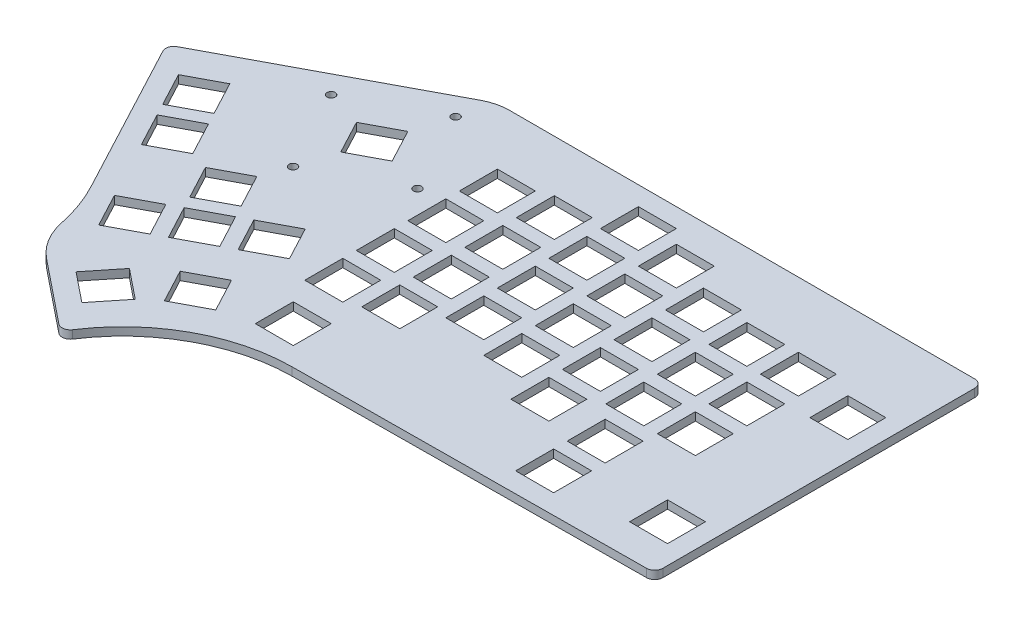
SolidWorks part; units mm, degrees
ref_plane "Front Plane" through (0, 0, 0) normal (0, 0, 1) x (1, 0, 0)
ref_plane "Top Plane" through (0, 0, 0) normal (0, 1, 0) x (1, 0, 0)
ref_plane "Right Plane" through (0, 0, 0) normal (1, 0, 0) x (0, 0, -1)
sketch "Main" plane through (0, 0, 0) normal (0, 1, 0) x (1, 0, 0)
  line L0 (6.4754, 3.5) -> (12.8, 6.5) construction
  line L1 (0, 0) -> (18, 0) construction
  line L2 (0, 0) -> (0, 18) construction
  line L3 (0, 18) -> (18, 18) construction
  line L4 (18, 0) -> (18, 18) construction
  line L5 (2, 16) -> (16, 16)
  line L6 (2, 16) -> (2, 2)
  line L7 (2, 2) -> (16, 2)
  line L8 (16, 16) -> (16, 2)
  line L18 (9, 9) -> (6.4754, 3.5) construction
  line L20 (9, 9) -> (12.8, 6.5) construction
  line L22 (25.4754, 5.5) -> (31.8, 8.5) construction
  line L23 (19, 2) -> (37, 2) construction
  line L24 (19, 2) -> (19, 20) construction
  line L25 (19, 20) -> (37, 20) construction
  line L26 (37, 2) -> (37, 20) construction
  line L27 (21, 18) -> (35, 18)
  line L28 (21, 18) -> (21, 4)
  line L29 (21, 4) -> (35, 4)
  line L30 (35, 18) -> (35, 4)
  line L31 (28, 11) -> (25.4754, 5.5) construction
  line L32 (28, 11) -> (31.8, 8.5) construction
  line L33 (44.4754, 17.5) -> (50.8, 20.5) construction
  line L34 (38, 14) -> (56, 14) construction
  line L35 (38, 14) -> (38, 32) construction
  line L36 (38, 32) -> (56, 32) construction
  line L37 (56, 14) -> (56, 32) construction
  line L38 (40, 30) -> (54, 30)
  line L39 (40, 30) -> (40, 16)
  line L40 (40, 16) -> (54, 16)
  line L41 (54, 30) -> (54, 16)
  line L42 (47, 23) -> (44.4754, 17.5) construction
  line L43 (47, 23) -> (50.8, 20.5) construction
  line L44 (63.4754, 12.5) -> (69.8, 15.5) construction
  line L45 (57, 9) -> (75, 9) construction
  line L46 (57, 9) -> (57, 27) construction
  line L47 (57, 27) -> (75, 27) construction
  line L48 (75, 9) -> (75, 27) construction
  line L49 (59, 25) -> (73, 25)
  line L50 (59, 25) -> (59, 11)
  line L51 (59, 11) -> (73, 11)
  line L52 (73, 25) -> (73, 11)
  line L53 (66, 18) -> (63.4754, 12.5) construction
  line L54 (66, 18) -> (69.8, 15.5) construction
  line L55 (82.4754, 3.5) -> (88.8, 6.5) construction
  line L56 (76, 0) -> (94, 0) construction
  line L57 (76, 0) -> (76, 18) construction
  line L58 (76, 18) -> (94, 18) construction
  line L59 (94, 0) -> (94, 18) construction
  line L60 (78, 16) -> (92, 16)
  line L61 (78, 16) -> (78, 2)
  line L62 (78, 2) -> (92, 2)
  line L63 (92, 16) -> (92, 2)
  line L64 (85, 9) -> (82.4754, 3.5) construction
  line L65 (85, 9) -> (88.8, 6.5) construction
  line L66 (101.4754, 0.5) -> (107.8, 3.5) construction
  line L67 (95, -3) -> (113, -3) construction
  line L68 (95, -3) -> (95, 15) construction
  line L69 (95, 15) -> (113, 15) construction
  line L70 (113, -3) -> (113, 15) construction
  line L71 (97, 13) -> (111, 13)
  line L72 (97, 13) -> (97, -1)
  line L73 (97, -1) -> (111, -1)
  line L74 (111, 13) -> (111, -1)
  line L75 (104, 6) -> (101.4754, 0.5) construction
  line L76 (104, 6) -> (107.8, 3.5) construction
  line L77 (120.4754, 0.5) -> (126.8, 3.5) construction
  line L78 (114, -3) -> (132, -3) construction
  line L79 (114, -3) -> (114, 15) construction
  line L80 (114, 15) -> (132, 15) construction
  line L81 (132, -3) -> (132, 15) construction
  line L82 (116, 13) -> (130, 13)
  line L83 (116, 13) -> (116, -1)
  line L84 (116, -1) -> (130, -1)
  line L85 (130, 13) -> (130, -1)
  line L86 (123, 6) -> (120.4754, 0.5) construction
  line L87 (123, 6) -> (126.8, 3.5) construction
  line L88 (2, -3) -> (16, -3)
  line L89 (2, -3) -> (2, -17)
  line L90 (2, -17) -> (16, -17)
  line L91 (16, -3) -> (16, -17)
  line L92 (21, -1) -> (35, -1)
  line L93 (21, -1) -> (21, -15)
  line L94 (21, -15) -> (35, -15)
  line L95 (35, -1) -> (35, -15)
  line L96 (40, 11) -> (54, 11)
  line L97 (40, 11) -> (40, -3)
  line L98 (40, -3) -> (54, -3)
  line L99 (54, 11) -> (54, -3)
  line L100 (59, 6) -> (73, 6)
  line L101 (59, 6) -> (59, -8)
  line L102 (59, -8) -> (73, -8)
  line L103 (73, 6) -> (73, -8)
  line L104 (78, -3) -> (92, -3)
  line L105 (78, -3) -> (78, -17)
  line L106 (78, -17) -> (92, -17)
  line L107 (92, -3) -> (92, -17)
  line L108 (97, -6) -> (111, -6)
  line L109 (97, -6) -> (97, -20)
  line L110 (97, -20) -> (111, -20)
  line L111 (111, -6) -> (111, -20)
  line L112 (116, -6) -> (130, -6)
  line L113 (116, -6) -> (116, -20)
  line L114 (116, -20) -> (130, -20)
  line L115 (130, -6) -> (130, -20)
  line L116 (6.4754, -15.5) -> (12.8, -12.5) construction
  line L117 (0, -19) -> (18, -19) construction
  line L118 (0, -19) -> (0, -1) construction
  line L119 (0, -1) -> (18, -1) construction
  line L120 (18, -19) -> (18, -1) construction
  line L121 (9, -10) -> (6.4754, -15.5) construction
  line L122 (9, -10) -> (12.8, -12.5) construction
  line L123 (25.4754, -13.5) -> (31.8, -10.5) construction
  line L124 (19, -17) -> (37, -17) construction
  line L125 (19, -17) -> (19, 1) construction
  line L126 (19, 1) -> (37, 1) construction
  line L127 (37, -17) -> (37, 1) construction
  line L128 (28, -8) -> (25.4754, -13.5) construction
  line L129 (28, -8) -> (31.8, -10.5) construction
  line L130 (44.4754, -1.5) -> (50.8, 1.5) construction
  line L131 (38, -5) -> (56, -5) construction
  line L132 (38, -5) -> (38, 13) construction
  line L133 (38, 13) -> (56, 13) construction
  line L134 (56, -5) -> (56, 13) construction
  line L135 (47, 4) -> (44.4754, -1.5) construction
  line L136 (47, 4) -> (50.8, 1.5) construction
  line L137 (63.4754, -6.5) -> (69.8, -3.5) construction
  line L138 (57, -10) -> (75, -10) construction
  line L139 (57, -10) -> (57, 8) construction
  line L140 (57, 8) -> (75, 8) construction
  line L141 (75, -10) -> (75, 8) construction
  line L142 (66, -1) -> (63.4754, -6.5) construction
  line L143 (66, -1) -> (69.8, -3.5) construction
  line L144 (82.4754, -15.5) -> (88.8, -12.5) construction
  line L145 (76, -19) -> (94, -19) construction
  line L146 (76, -19) -> (76, -1) construction
  line L147 (76, -1) -> (94, -1) construction
  line L148 (94, -19) -> (94, -1) construction
  line L149 (85, -10) -> (82.4754, -15.5) construction
  line L150 (85, -10) -> (88.8, -12.5) construction
  line L151 (101.4754, -18.5) -> (107.8, -15.5) construction
  line L152 (95, -22) -> (113, -22) construction
  line L153 (95, -22) -> (95, -4) construction
  line L154 (95, -4) -> (113, -4) construction
  line L155 (113, -22) -> (113, -4) construction
  line L156 (104, -13) -> (101.4754, -18.5) construction
  line L157 (104, -13) -> (107.8, -15.5) construction
  line L158 (120.4754, -18.5) -> (126.8, -15.5) construction
  line L159 (114, -22) -> (132, -22) construction
  line L160 (114, -22) -> (114, -4) construction
  line L161 (114, -4) -> (132, -4) construction
  line L162 (132, -22) -> (132, -4) construction
  line L163 (123, -13) -> (120.4754, -18.5) construction
  line L164 (123, -13) -> (126.8, -15.5) construction
  line L165 (2, -22) -> (16, -22)
  line L166 (2, -22) -> (2, -36)
  line L167 (2, -36) -> (16, -36)
  line L168 (16, -22) -> (16, -36)
  line L169 (21, -20) -> (35, -20)
  line L170 (21, -20) -> (21, -34)
  line L171 (21, -34) -> (35, -34)
  line L172 (35, -20) -> (35, -34)
  line L173 (40, -8) -> (54, -8)
  line L174 (40, -8) -> (40, -22)
  line L175 (40, -22) -> (54, -22)
  line L176 (54, -8) -> (54, -22)
  line L177 (59, -13) -> (73, -13)
  line L178 (59, -13) -> (59, -27)
  line L179 (59, -27) -> (73, -27)
  line L180 (73, -13) -> (73, -27)
  line L181 (78, -22) -> (92, -22)
  line L182 (78, -22) -> (78, -36)
  line L183 (78, -36) -> (92, -36)
  line L184 (92, -22) -> (92, -36)
  line L185 (97, -25) -> (111, -25)
  line L186 (97, -25) -> (97, -39)
  line L187 (97, -39) -> (111, -39)
  line L188 (111, -25) -> (111, -39)
  line L189 (116, -25) -> (130, -25)
  line L190 (116, -25) -> (116, -39)
  line L191 (116, -39) -> (130, -39)
  line L192 (130, -25) -> (130, -39)
  line L193 (6.4754, -34.5) -> (12.8, -31.5) construction
  line L194 (0, -38) -> (18, -38) construction
  line L195 (0, -38) -> (0, -20) construction
  line L196 (0, -20) -> (18, -20) construction
  line L197 (18, -38) -> (18, -20) construction
  line L198 (9, -29) -> (6.4754, -34.5) construction
  line L199 (9, -29) -> (12.8, -31.5) construction
  line L200 (25.4754, -32.5) -> (31.8, -29.5) construction
  line L201 (19, -36) -> (37, -36) construction
  line L202 (19, -36) -> (19, -18) construction
  line L203 (19, -18) -> (37, -18) construction
  line L204 (37, -36) -> (37, -18) construction
  line L205 (28, -27) -> (25.4754, -32.5) construction
  line L206 (28, -27) -> (31.8, -29.5) construction
  line L207 (44.4754, -20.5) -> (50.8, -17.5) construction
  line L208 (38, -24) -> (56, -24) construction
  line L209 (38, -24) -> (38, -6) construction
  line L210 (38, -6) -> (56, -6) construction
  line L211 (56, -24) -> (56, -6) construction
  line L212 (47, -15) -> (44.4754, -20.5) construction
  line L213 (47, -15) -> (50.8, -17.5) construction
  line L214 (63.4754, -25.5) -> (69.8, -22.5) construction
  line L215 (57, -29) -> (75, -29) construction
  line L216 (57, -29) -> (57, -11) construction
  line L217 (57, -11) -> (75, -11) construction
  line L218 (75, -29) -> (75, -11) construction
  line L219 (66, -20) -> (63.4754, -25.5) construction
  line L220 (66, -20) -> (69.8, -22.5) construction
  line L221 (82.4754, -34.5) -> (88.8, -31.5) construction
  line L222 (76, -38) -> (94, -38) construction
  line L223 (76, -38) -> (76, -20) construction
  line L224 (76, -20) -> (94, -20) construction
  line L225 (94, -38) -> (94, -20) construction
  line L226 (85, -29) -> (82.4754, -34.5) construction
  line L227 (85, -29) -> (88.8, -31.5) construction
  line L228 (101.4754, -37.5) -> (107.8, -34.5) construction
  line L229 (95, -41) -> (113, -41) construction
  line L230 (95, -41) -> (95, -23) construction
  line L231 (95, -23) -> (113, -23) construction
  line L232 (113, -41) -> (113, -23) construction
  line L233 (104, -32) -> (101.4754, -37.5) construction
  line L234 (104, -32) -> (107.8, -34.5) construction
  line L235 (120.4754, -37.5) -> (126.8, -34.5) construction
  line L236 (114, -41) -> (132, -41) construction
  line L237 (114, -41) -> (114, -23) construction
  line L238 (114, -23) -> (132, -23) construction
  line L239 (132, -41) -> (132, -23) construction
  line L240 (123, -32) -> (120.4754, -37.5) construction
  line L241 (123, -32) -> (126.8, -34.5) construction
  line L242 (2, -41) -> (16, -41)
  line L243 (2, -41) -> (2, -55)
  line L244 (2, -55) -> (16, -55)
  line L245 (16, -41) -> (16, -55)
  line L246 (21, -39) -> (35, -39)
  line L247 (21, -39) -> (21, -53)
  line L248 (21, -53) -> (35, -53)
  line L249 (35, -39) -> (35, -53)
  line L250 (40, -27) -> (54, -27)
  line L251 (40, -27) -> (40, -41)
  line L252 (40, -41) -> (54, -41)
  line L253 (54, -27) -> (54, -41)
  line L254 (59, -32) -> (73, -32)
  line L255 (59, -32) -> (59, -46)
  line L256 (59, -46) -> (73, -46)
  line L257 (73, -32) -> (73, -46)
  line L258 (78, -41) -> (92, -41)
  line L259 (78, -41) -> (78, -55)
  line L260 (78, -55) -> (92, -55)
  line L261 (92, -41) -> (92, -55)
  line L270 (6.4754, -53.5) -> (12.8, -50.5) construction
  line L271 (0, -57) -> (18, -57) construction
  line L272 (0, -57) -> (0, -39) construction
  line L273 (0, -39) -> (18, -39) construction
  line L274 (18, -57) -> (18, -39) construction
  line L275 (9, -48) -> (6.4754, -53.5) construction
  line L276 (9, -48) -> (12.8, -50.5) construction
  line L277 (25.4754, -51.5) -> (31.8, -48.5) construction
  line L278 (19, -55) -> (37, -55) construction
  line L279 (19, -55) -> (19, -37) construction
  line L280 (19, -37) -> (37, -37) construction
  line L281 (37, -55) -> (37, -37) construction
  line L282 (28, -46) -> (25.4754, -51.5) construction
  line L283 (28, -46) -> (31.8, -48.5) construction
  line L284 (44.4754, -39.5) -> (50.8, -36.5) construction
  line L285 (38, -43) -> (56, -43) construction
  line L286 (38, -43) -> (38, -25) construction
  line L287 (38, -25) -> (56, -25) construction
  line L288 (56, -43) -> (56, -25) construction
  line L289 (47, -34) -> (44.4754, -39.5) construction
  line L290 (47, -34) -> (50.8, -36.5) construction
  line L291 (63.4754, -44.5) -> (69.8, -41.5) construction
  line L292 (57, -48) -> (75, -48) construction
  line L293 (57, -48) -> (57, -30) construction
  line L294 (57, -30) -> (75, -30) construction
  line L295 (75, -48) -> (75, -30) construction
  line L296 (66, -39) -> (63.4754, -44.5) construction
  line L297 (66, -39) -> (69.8, -41.5) construction
  line L298 (82.4754, -53.5) -> (88.8, -50.5) construction
  line L299 (76, -57) -> (94, -57) construction
  line L300 (76, -57) -> (76, -39) construction
  line L301 (76, -39) -> (94, -39) construction
  line L302 (94, -57) -> (94, -39) construction
  line L303 (85, -48) -> (82.4754, -53.5) construction
  line L304 (85, -48) -> (88.8, -50.5) construction
  line L319 (97, -44) -> (111, -44)
  line L320 (97, -44) -> (97, -58)
  line L321 (97, -58) -> (111, -58)
  line L322 (111, -44) -> (111, -58)
  line L323 (116, -44) -> (130, -44)
  line L324 (116, -44) -> (116, -58)
  line L325 (116, -58) -> (130, -58)
  line L326 (130, -44) -> (130, -58)
  line L327 (101.4754, -56.5) -> (107.8, -53.5) construction
  line L328 (95, -60) -> (113, -60) construction
  line L329 (95, -60) -> (95, -42) construction
  line L330 (95, -42) -> (113, -42) construction
  line L331 (113, -60) -> (113, -42) construction
  line L332 (104, -51) -> (101.4754, -56.5) construction
  line L333 (104, -51) -> (107.8, -53.5) construction
  line L334 (120.4754, -56.5) -> (126.8, -53.5) construction
  line L335 (114, -60) -> (132, -60) construction
  line L336 (114, -60) -> (114, -42) construction
  line L337 (114, -42) -> (132, -42) construction
  line L338 (132, -60) -> (132, -42) construction
  line L339 (123, -51) -> (120.4754, -56.5) construction
  line L340 (123, -51) -> (126.8, -53.5) construction
  circle A0 centre (9, 9) radius 2 construction
  circle A1 centre (6.4754, 3.5) radius 1.5 construction
  circle A2 centre (12.8, 6.5) radius 1.5 construction
  circle A6 centre (28, 11) radius 2 construction
  circle A7 centre (25.4754, 5.5) radius 1.5 construction
  circle A8 centre (31.8, 8.5) radius 1.5 construction
  circle A9 centre (47, 23) radius 2 construction
  circle A10 centre (44.4754, 17.5) radius 1.5 construction
  circle A11 centre (50.8, 20.5) radius 1.5 construction
  circle A12 centre (66, 18) radius 2 construction
  circle A13 centre (63.4754, 12.5) radius 1.5 construction
  circle A14 centre (69.8, 15.5) radius 1.5 construction
  circle A15 centre (85, 9) radius 2 construction
  circle A16 centre (82.4754, 3.5) radius 1.5 construction
  circle A17 centre (88.8, 6.5) radius 1.5 construction
  circle A18 centre (104, 6) radius 2 construction
  circle A19 centre (101.4754, 0.5) radius 1.5 construction
  circle A20 centre (107.8, 3.5) radius 1.5 construction
  circle A21 centre (123, 6) radius 2 construction
  circle A22 centre (120.4754, 0.5) radius 1.5 construction
  circle A23 centre (126.8, 3.5) radius 1.5 construction
  circle A24 centre (9, -10) radius 2 construction
  circle A25 centre (6.4754, -15.5) radius 1.5 construction
  circle A26 centre (12.8, -12.5) radius 1.5 construction
  circle A27 centre (28, -8) radius 2 construction
  circle A28 centre (25.4754, -13.5) radius 1.5 construction
  circle A29 centre (31.8, -10.5) radius 1.5 construction
  circle A30 centre (47, 4) radius 2 construction
  circle A31 centre (44.4754, -1.5) radius 1.5 construction
  circle A32 centre (50.8, 1.5) radius 1.5 construction
  circle A33 centre (66, -1) radius 2 construction
  circle A34 centre (63.4754, -6.5) radius 1.5 construction
  circle A35 centre (69.8, -3.5) radius 1.5 construction
  circle A36 centre (85, -10) radius 2 construction
  circle A37 centre (82.4754, -15.5) radius 1.5 construction
  circle A38 centre (88.8, -12.5) radius 1.5 construction
  circle A39 centre (104, -13) radius 2 construction
  circle A40 centre (101.4754, -18.5) radius 1.5 construction
  circle A41 centre (107.8, -15.5) radius 1.5 construction
  circle A42 centre (123, -13) radius 2 construction
  circle A43 centre (120.4754, -18.5) radius 1.5 construction
  circle A44 centre (126.8, -15.5) radius 1.5 construction
  circle A45 centre (9, -29) radius 2 construction
  circle A46 centre (6.4754, -34.5) radius 1.5 construction
  circle A47 centre (12.8, -31.5) radius 1.5 construction
  circle A48 centre (28, -27) radius 2 construction
  circle A49 centre (25.4754, -32.5) radius 1.5 construction
  circle A50 centre (31.8, -29.5) radius 1.5 construction
  circle A51 centre (47, -15) radius 2 construction
  circle A52 centre (44.4754, -20.5) radius 1.5 construction
  circle A53 centre (50.8, -17.5) radius 1.5 construction
  circle A54 centre (66, -20) radius 2 construction
  circle A55 centre (63.4754, -25.5) radius 1.5 construction
  circle A56 centre (69.8, -22.5) radius 1.5 construction
  circle A57 centre (85, -29) radius 2 construction
  circle A58 centre (82.4754, -34.5) radius 1.5 construction
  circle A59 centre (88.8, -31.5) radius 1.5 construction
  circle A60 centre (104, -32) radius 2 construction
  circle A61 centre (101.4754, -37.5) radius 1.5 construction
  circle A62 centre (107.8, -34.5) radius 1.5 construction
  circle A63 centre (123, -32) radius 2 construction
  circle A64 centre (120.4754, -37.5) radius 1.5 construction
  circle A65 centre (126.8, -34.5) radius 1.5 construction
  circle A66 centre (9, -48) radius 2 construction
  circle A67 centre (6.4754, -53.5) radius 1.5 construction
  circle A68 centre (12.8, -50.5) radius 1.5 construction
  circle A69 centre (28, -46) radius 2 construction
  circle A70 centre (25.4754, -51.5) radius 1.5 construction
  circle A71 centre (31.8, -48.5) radius 1.5 construction
  circle A72 centre (47, -34) radius 2 construction
  circle A73 centre (44.4754, -39.5) radius 1.5 construction
  circle A74 centre (50.8, -36.5) radius 1.5 construction
  circle A75 centre (66, -39) radius 2 construction
  circle A76 centre (63.4754, -44.5) radius 1.5 construction
  circle A77 centre (69.8, -41.5) radius 1.5 construction
  circle A78 centre (85, -48) radius 2 construction
  circle A79 centre (82.4754, -53.5) radius 1.5 construction
  circle A80 centre (88.8, -50.5) radius 1.5 construction
  circle A87 centre (104, -51) radius 2 construction
  circle A88 centre (101.4754, -56.5) radius 1.5 construction
  circle A89 centre (107.8, -53.5) radius 1.5 construction
  circle A90 centre (123, -51) radius 2 construction
  circle A91 centre (120.4754, -56.5) radius 1.5 construction
  circle A92 centre (126.8, -53.5) radius 1.5 construction
  point P9 (9, 16)
  point P10 (9, 18)
  point P11 (2, 9)
  point P12 (0, 9)
  point P30 (28, 18)
  point P31 (28, 20)
  point P32 (21, 11)
  point P33 (19, 11)
  point P46 (47, 30)
  point P47 (47, 32)
  point P48 (40, 23)
  point P49 (38, 23)
  point P64 (66, 25)
  point P65 (66, 27)
  point P66 (59, 18)
  point P67 (57, 18)
  point P82 (85, 16)
  point P83 (85, 18)
  point P84 (78, 9)
  point P85 (76, 9)
  point P100 (104, 13)
  point P101 (104, 15)
  point P102 (97, 6)
  point P103 (95, 6)
  point P118 (123, 13)
  point P119 (123, 15)
  point P120 (116, 6)
  point P121 (114, 6)
  dimension "D6" = 4
  dimension "D7" = 3
  dimension "D10" = 1
  dimension "D11" = 5
  dimension "D1" = 18
  dimension "D2" = 14
  dimension "D3" = 3.2
  dimension "D4" = 4.5
  dimension "D5" = 7
  dimension "D8" = 1
  dimension "D9" = 12
  dimension "D12" = 1
  dimension "D13" = 2
  dimension "D14" = 1
  dimension "D15" = 9
  dimension "D16" = 1
  dimension "D17" = 3
  dimension "D18" = 1
  dimension "D20" = 1
  dimension "D19" = 4
sketch "EntBckSp" plane through (0, 0, 0) normal (0, 1, 0) x (1, 0, 0)
  line L0 (0, 0) -> (18, 0) construction
  line L1 (139, 8.25) -> (153, 8.25)
  line L2 (139, 8.25) -> (139, -5.75)
  line L3 (139, -5.75) -> (153, -5.75)
  line L4 (153, 8.25) -> (153, -5.75)
  line L5 (137, 15) -> (155, 15) construction
  line L6 (137, 15) -> (137, -12.5) construction
  line L7 (137, -12.5) -> (155, -12.5) construction
  line L8 (155, 15) -> (155, -12.5) construction
  line L9 (2, 2) -> (16, 2) construction
  line L10 (143.4754, -4.25) -> (146, 1.25) construction
  line L11 (146, 1.25) -> (149.8, -1.25) construction
  line L12 (149.8, -1.25) -> (143.4754, -4.25) construction
  line L13 (6.4754, 3.5) -> (12.8, 6.5) construction
  line L14 (9, 9) -> (6.4754, 3.5) construction
  line L15 (9, 9) -> (12.8, 6.5) construction
  line L16 (114, 15) -> (132, 15) construction
  line L17 (132, -3) -> (132, 15) construction
  line L18 (101.75, -44) -> (115.75, -44)
  line L19 (101.75, -44) -> (101.75, -58)
  line L20 (101.75, -58) -> (115.75, -58)
  line L21 (115.75, -44) -> (115.75, -58)
  line L22 (95, -42) -> (122.5, -42) construction
  line L23 (95, -42) -> (95, -60) construction
  line L24 (95, -60) -> (122.5, -60) construction
  line L25 (122.5, -42) -> (122.5, -60) construction
  line L26 (106.2254, -56.5) -> (108.75, -51) construction
  line L27 (108.75, -51) -> (112.55, -53.5) construction
  line L28 (112.55, -53.5) -> (106.2254, -56.5) construction
  line L29 (95, -41) -> (95, -23) construction
  line L30 (95, -41) -> (113, -41) construction
  line L31 (101.75, -63) -> (115.75, -63)
  line L32 (101.75, -63) -> (101.75, -77)
  line L33 (101.75, -77) -> (115.75, -77)
  line L34 (115.75, -63) -> (115.75, -77)
  line L35 (95, -61) -> (122.5, -61) construction
  line L36 (95, -61) -> (95, -79) construction
  line L37 (95, -79) -> (122.5, -79) construction
  line L38 (122.5, -61) -> (122.5, -79) construction
  line L39 (106.2254, -75.5) -> (108.75, -70) construction
  line L40 (108.75, -70) -> (112.55, -72.5) construction
  line L41 (112.55, -72.5) -> (106.2254, -75.5) construction
  line L42 (139, -58.25) -> (153, -58.25)
  line L43 (139, -58.25) -> (139, -72.25)
  line L44 (139, -72.25) -> (153, -72.25)
  line L45 (153, -58.25) -> (153, -72.25)
  line L46 (137, -51.5) -> (155, -51.5) construction
  line L47 (137, -51.5) -> (137, -79) construction
  line L48 (137, -79) -> (155, -79) construction
  line L49 (155, -51.5) -> (155, -79) construction
  line L50 (143.4754, -70.75) -> (146, -65.25) construction
  line L51 (146, -65.25) -> (149.8, -67.75) construction
  line L52 (149.8, -67.75) -> (143.4754, -70.75) construction
  line L66 (6.75, -64) -> (20.75, -64)
  line L67 (6.75, -64) -> (6.75, -78)
  line L68 (6.75, -78) -> (20.75, -78)
  line L69 (20.75, -64) -> (20.75, -78)
  line L70 (0, -62) -> (27.5, -62) construction
  line L71 (0, -62) -> (0, -80) construction
  line L72 (0, -80) -> (27.5, -80) construction
  line L73 (27.5, -62) -> (27.5, -80) construction
  line L74 (11.2254, -76.5) -> (13.75, -71) construction
  line L75 (13.75, -71) -> (17.55, -73.5) construction
  line L76 (17.55, -73.5) -> (11.2254, -76.5) construction
  line L77 (0, -57) -> (18, -57) construction
  line L78 (0, -57) -> (0, -39) construction
  circle A0 centre (146, 1.25) radius 2 construction
  circle A1 centre (143.4754, -4.25) radius 1.5 construction
  circle A2 centre (149.8, -1.25) radius 1.5 construction
  circle A3 centre (9, 9) radius 2 construction
  circle A4 centre (6.4754, 3.5) radius 1.5 construction
  circle A5 centre (108.75, -51) radius 2 construction
  circle A6 centre (106.2254, -56.5) radius 1.5 construction
  circle A7 centre (112.55, -53.5) radius 1.5 construction
  circle A8 centre (108.75, -70) radius 2 construction
  circle A9 centre (106.2254, -75.5) radius 1.5 construction
  circle A10 centre (112.55, -72.5) radius 1.5 construction
  circle A11 centre (146, -65.25) radius 2 construction
  circle A12 centre (143.4754, -70.75) radius 1.5 construction
  circle A13 centre (149.8, -67.75) radius 1.5 construction
  circle A17 centre (13.75, -71) radius 2 construction
  circle A18 centre (11.2254, -76.5) radius 1.5 construction
  circle A19 centre (17.55, -73.5) radius 1.5 construction
  point P14 (146, 8.25)
  point P15 (146, 15)
  point P16 (139, 1.25)
  point P17 (137, 1.25)
  point P51 (108.75, -44)
  point P52 (108.75, -42)
  point P53 (101.75, -51)
  point P54 (95, -51)
  point P87 (146, -58.25)
  point P88 (146, -51.5)
  point P89 (139, -65.25)
  point P90 (137, -65.25)
  point P105 (13.75, -64)
  point P106 (13.75, -62)
  point P107 (6.75, -71)
  point P108 (0, -71)
  dimension "D1" = 27.5
  dimension "D2" = 5
  dimension "D3" = 1
  dimension "D5" = 1
  dimension "D7" = 5
  dimension "D4" = 2
sketch "MoLngGo" plane through (0, 0, 0) normal (0, 1, 0) x (1, 0, 0)
  line L0 (-23.8647, -75.115) -> (-11.5011, -68.5469)
  line L1 (-23.8647, -75.115) -> (-17.2967, -87.4787)
  line L2 (-11.5011, -68.5469) -> (-4.933, -80.9106)
  line L3 (-17.2967, -87.4787) -> (-4.933, -80.9106)
  line L4 (-28.7977, -70.0922) -> (-12.9016, -61.6476) construction
  line L5 (-28.7977, -70.0922) -> (-15.8962, -94.378) construction
  line L6 (-12.9016, -61.6476) -> (0, -85.9334) construction
  line L7 (-15.8962, -94.378) -> (0, -85.9334) construction
  line L8 (-12.9016, -61.6476) -> (-15.8962, -94.378) construction
  line L9 (-23.8647, -75.115) -> (-4.933, -80.9106) construction
  line L10 (0, -62) -> (0, -80) construction
  line L11 (0, -80) -> (27.5, -80) construction
  line L12 (6.75, -78) -> (20.75, -78) construction
  line L13 (-14.3989, -78.0128) -> (13.75, -131) construction
  line L14 (-14.048, -84.0544) -> (-9.8701, -78.4379) construction
  line L15 (-9.8701, -78.4379) -> (-14.3989, -78.0128) construction
  line L16 (-14.3989, -78.0128) -> (-14.048, -84.0544) construction
  line L17 (17.55, -73.5) -> (11.2254, -76.5) construction
  line L18 (11.2254, -76.5) -> (13.75, -71) construction
  line L19 (13.75, -71) -> (17.55, -73.5) construction
  line L20 (-42.8638, -94.4914) -> (-34.0949, -83.5778)
  line L21 (-42.8638, -94.4914) -> (-31.9502, -103.2603)
  line L22 (-34.0949, -83.5778) -> (-23.1813, -92.3467)
  line L23 (-31.9502, -103.2603) -> (-23.1813, -92.3467)
  line L24 (-49.3784, -91.8226) -> (-38.1041, -77.7908) construction
  line L25 (-49.3784, -91.8226) -> (-27.941, -109.0472) construction
  line L26 (-38.1041, -77.7908) -> (-16.6667, -95.0154) construction
  line L27 (-27.941, -109.0472) -> (-16.6667, -95.0154) construction
  line L28 (-38.1041, -77.7908) -> (-27.941, -109.0472) construction
  line L29 (-42.8638, -94.4914) -> (-23.1813, -92.3467) construction
  line L30 (-33.0225, -93.419) -> (13.75, -131) construction
  line L31 (-30.3163, -98.8319) -> (-28.6936, -92.0226) construction
  line L32 (-28.6936, -92.0226) -> (-33.0225, -93.419) construction
  line L33 (-33.0225, -93.419) -> (-30.3163, -98.8319) construction
  line L34 (-26.6363, -45.1647) -> (-14.2726, -38.5966)
  line L35 (-26.6363, -45.1647) -> (-20.0682, -57.5283)
  line L36 (-14.2726, -38.5966) -> (-7.7045, -50.9603)
  line L37 (-20.0682, -57.5283) -> (-7.7045, -50.9603)
  line L38 (-29.3408, -44.3367) -> (-13.4447, -35.8921) construction
  line L39 (-29.3408, -44.3367) -> (-20.8962, -60.2329) construction
  line L40 (-13.4447, -35.8921) -> (-5, -51.7882) construction
  line L41 (-20.8962, -60.2329) -> (-5, -51.7882) construction
  line L42 (-13.4447, -35.8921) -> (-20.8962, -60.2329) construction
  line L43 (-26.6363, -45.1647) -> (-7.7045, -50.9603) construction
  line L44 (-16.8196, -54.104) -> (-12.6417, -48.4875) construction
  line L45 (-12.6417, -48.4875) -> (-17.1704, -48.0625) construction
  line L46 (-17.1704, -48.0625) -> (-16.8196, -54.104) construction
  line L47 (-43.4156, -54.0785) -> (-31.0519, -47.5104)
  line L48 (-43.4156, -54.0785) -> (-36.8475, -66.4422)
  line L49 (-31.0519, -47.5104) -> (-24.4838, -59.8741)
  line L50 (-36.8475, -66.4422) -> (-24.4838, -59.8741)
  line L51 (-46.1201, -53.2505) -> (-30.2239, -44.8059) construction
  line L52 (-46.1201, -53.2505) -> (-37.6754, -69.1467) construction
  line L53 (-30.2239, -44.8059) -> (-21.7793, -60.702) construction
  line L54 (-37.6754, -69.1467) -> (-21.7793, -60.702) construction
  line L55 (-30.2239, -44.8059) -> (-37.6754, -69.1467) construction
  line L56 (-43.4156, -54.0785) -> (-24.4838, -59.8741) construction
  line L57 (-33.5989, -63.0178) -> (-29.421, -57.4013) construction
  line L58 (-29.421, -57.4013) -> (-33.9497, -56.9763) construction
  line L59 (-33.9497, -56.9763) -> (-33.5989, -63.0178) construction
  line L60 (-60.1948, -62.9923) -> (-47.8312, -56.4242)
  line L61 (-60.1948, -62.9923) -> (-53.6268, -75.356)
  line L62 (-47.8312, -56.4242) -> (-41.2631, -68.7879)
  line L63 (-53.6268, -75.356) -> (-41.2631, -68.7879)
  line L64 (-62.8994, -62.1643) -> (-47.0032, -53.7197) construction
  line L65 (-62.8994, -62.1643) -> (-54.4547, -78.0605) construction
  line L66 (-47.0032, -53.7197) -> (-38.5586, -69.6158) construction
  line L67 (-54.4547, -78.0605) -> (-38.5586, -69.6158) construction
  line L68 (-47.0032, -53.7197) -> (-54.4547, -78.0605) construction
  line L69 (-60.1948, -62.9923) -> (-41.2631, -68.7879) construction
  line L70 (-50.3781, -71.9316) -> (-46.2002, -66.3151) construction
  line L71 (-46.2002, -66.3151) -> (-50.729, -65.8901) construction
  line L72 (-50.729, -65.8901) -> (-50.3781, -71.9316) construction
  line L73 (0, -57) -> (0, -39) construction
  line L74 (-52.3294, -37.2992) -> (-39.9657, -30.7311)
  line L75 (-52.3294, -37.2992) -> (-45.7613, -49.6629)
  line L76 (-39.9657, -30.7311) -> (-33.3976, -43.0948)
  line L77 (-45.7613, -49.6629) -> (-33.3976, -43.0948)
  line L78 (-55.0339, -36.4713) -> (-39.1377, -28.0266) construction
  line L79 (-55.0339, -36.4713) -> (-46.5892, -52.3674) construction
  line L80 (-46.5892, -52.3674) -> (-30.6931, -43.9228) construction
  line L81 (-39.1377, -28.0266) -> (-46.5892, -52.3674) construction
  line L82 (-52.3294, -37.2992) -> (-33.3976, -43.0948) construction
  line L83 (-42.5127, -46.2386) -> (-38.3348, -40.622) construction
  line L84 (-38.3348, -40.622) -> (-42.8635, -40.197) construction
  line L85 (-42.8635, -40.197) -> (-42.5127, -46.2386) construction
  line L86 (-39.1377, -28.0266) -> (-30.6931, -43.9228) construction
  line L96 (0, -19) -> (0, -1) construction
  line L98 (-38.8848, 4.9459) -> (-26.5211, 11.514)
  line L99 (-38.8848, 4.9459) -> (-32.3167, -7.4178)
  line L100 (-78.0224, -29.4337) -> (-65.6588, -22.8657)
  line L101 (-78.0224, -29.4337) -> (-71.4544, -41.7974)
  line L102 (-65.6588, -22.8657) -> (-59.0907, -35.2293)
  line L103 (-71.4544, -41.7974) -> (-59.0907, -35.2293)
  line L104 (-80.727, -28.6058) -> (-64.8308, -20.1611) construction
  line L105 (-80.727, -28.6058) -> (-72.2823, -44.5019) construction
  line L106 (-64.8308, -20.1611) -> (-56.3862, -36.0573) construction
  line L107 (-72.2823, -44.5019) -> (-56.3862, -36.0573) construction
  line L108 (-64.8308, -20.1611) -> (-72.2823, -44.5019) construction
  line L109 (-78.0224, -29.4337) -> (-59.0907, -35.2293) construction
  line L110 (-68.2057, -38.3731) -> (-64.0278, -32.7566) construction
  line L111 (-64.0278, -32.7566) -> (-68.5566, -32.3315) construction
  line L112 (-68.5566, -32.3315) -> (-68.2057, -38.3731) construction
  line L113 (-86.9362, -12.6545) -> (-74.5726, -6.0864)
  line L114 (-86.9362, -12.6545) -> (-80.3682, -25.0181)
  line L115 (-74.5726, -6.0864) -> (-68.0045, -18.4501)
  line L116 (-80.3682, -25.0181) -> (-68.0045, -18.4501)
  line L117 (-89.6408, -11.8265) -> (-73.7446, -3.3819) construction
  line L118 (-89.6408, -11.8265) -> (-81.1961, -27.7227) construction
  line L119 (-73.7446, -3.3819) -> (-65.3, -19.278) construction
  line L120 (-81.1961, -27.7227) -> (-65.3, -19.278) construction
  line L121 (-73.7446, -3.3819) -> (-81.1961, -27.7227) construction
  line L122 (-86.9362, -12.6545) -> (-68.0045, -18.4501) construction
  line L123 (-77.1195, -21.5938) -> (-72.9416, -15.9773) construction
  line L124 (-72.9416, -15.9773) -> (-77.4704, -15.5523) construction
  line L125 (-77.4704, -15.5523) -> (-77.1195, -21.5938) construction
  line L126 (-55.917, -36.9404) -> (-63.3685, -61.2812) construction
  line L127 (-69.1086, -46.213) -> (-50.1769, -52.0086) construction
  line L128 (-59.2919, -55.1524) -> (-55.114, -49.5359) construction
  line L129 (-55.114, -49.5359) -> (-59.6428, -49.1108) construction
  line L130 (-59.6428, -49.1108) -> (-59.2919, -55.1524) construction
  line L131 (-69.1086, -46.213) -> (-56.745, -39.6449) construction
  line L132 (-69.1086, -46.213) -> (-62.5406, -58.5767) construction
  line L133 (-71.8132, -45.3851) -> (-63.3685, -61.2812) construction
  line L134 (-63.3685, -61.2812) -> (-47.4724, -52.8366) construction
  line L135 (-56.745, -39.6449) -> (-50.1769, -52.0086) construction
  line L136 (-62.5406, -58.5767) -> (-50.1769, -52.0086) construction
  line L137 (-55.917, -36.9404) -> (-47.4724, -52.8366) construction
  line L138 (-71.8132, -45.3851) -> (-55.917, -36.9404) construction
  line L139 (-26.5211, 11.514) -> (-19.953, -0.8497)
  line L140 (-32.3167, -7.4178) -> (-19.953, -0.8497)
  line L141 (-41.5893, 5.7739) -> (-25.6932, 14.2185) construction
  line L142 (-41.5893, 5.7739) -> (-33.1447, -10.1223) construction
  line L143 (-25.6932, 14.2185) -> (-17.2485, -1.6776) construction
  line L144 (-33.1447, -10.1223) -> (-17.2485, -1.6776) construction
  line L145 (-25.6932, 14.2185) -> (-33.1447, -10.1223) construction
  line L146 (-38.8848, 4.9459) -> (-19.953, -0.8497) construction
  line L147 (-29.0681, -3.9934) -> (-24.8902, 1.6231) construction
  line L148 (-24.8902, 1.6231) -> (-29.4189, 2.0481) construction
  line L149 (-29.4189, 2.0481) -> (-29.0681, -3.9934) construction
  line L150 (-57.8165, 10.7415) -> (-20.7255, 30.4457) construction
  line L151 (-57.8165, 10.7415) -> (-38.1123, -26.3495) construction
  line L152 (-20.7255, 30.4457) -> (-1.0213, -6.6453) construction
  line L153 (-38.1123, -26.3495) -> (-1.0213, -6.6453) construction
  line L154 (-19.5668, -16.4974) -> (-39.271, 20.5936) construction
  line L155 (-25.6932, 14.2185) -> (-20.7255, 30.4457) construction
  circle A0 centre (13.75, -131) radius 60 construction
  circle A1 centre (-14.3989, -78.0128) radius 2 construction
  circle A2 centre (13.75, -71) radius 2 construction
  circle A3 centre (-14.048, -84.0544) radius 1.5 construction
  circle A4 centre (-9.8701, -78.4379) radius 1.5 construction
  circle A5 centre (11.2254, -76.5) radius 1.5 construction
  circle A6 centre (-33.0225, -93.419) radius 2 construction
  circle A7 centre (-30.3163, -98.8319) radius 1.5 construction
  circle A8 centre (-28.6936, -92.0226) radius 1.5 construction
  circle A9 centre (-17.1704, -48.0625) radius 2 construction
  circle A10 centre (-16.8196, -54.104) radius 1.5 construction
  circle A11 centre (-12.6417, -48.4875) radius 1.5 construction
  circle A12 centre (-33.9497, -56.9763) radius 2 construction
  circle A13 centre (-33.5989, -63.0178) radius 1.5 construction
  circle A14 centre (-29.421, -57.4013) radius 1.5 construction
  circle A15 centre (-50.729, -65.8901) radius 2 construction
  circle A16 centre (-50.3781, -71.9316) radius 1.5 construction
  circle A17 centre (-46.2002, -66.3151) radius 1.5 construction
  circle A18 centre (-42.8635, -40.197) radius 2 construction
  circle A19 centre (-42.5127, -46.2386) radius 1.5 construction
  circle A20 centre (-38.3348, -40.622) radius 1.5 construction
  circle A21 centre (-29.4189, 2.0481) radius 2 construction
  circle A22 centre (-29.0681, -3.9934) radius 1.5 construction
  circle A23 centre (-24.8902, 1.6231) radius 1.5 construction
  circle A24 centre (-68.5566, -32.3315) radius 2 construction
  circle A25 centre (-68.2057, -38.3731) radius 1.5 construction
  circle A26 centre (-64.0278, -32.7566) radius 1.5 construction
  circle A27 centre (-77.4704, -15.5523) radius 2 construction
  circle A28 centre (-77.1195, -21.5938) radius 1.5 construction
  circle A29 centre (-72.9416, -15.9773) radius 1.5 construction
  circle A30 centre (-59.6428, -49.1108) radius 2 construction
  circle A31 centre (-55.114, -49.5359) radius 1.5 construction
  circle A32 centre (-59.2919, -55.1524) radius 1.5 construction
  circle A33 centre (-29.4189, 2.0481) radius 24 construction
  circle A34 centre (-22.3936, 24.9968) radius 1.5
  circle A35 centre (-6.4702, -4.9772) radius 1.5
  circle A36 centre (-36.4443, -20.9006) radius 1.5
  circle A37 centre (-52.3677, 9.0734) radius 1.5
  point P2 (-14.3989, -78.0128)
  point P11 (-14.3989, -78.0128)
  point P39 (-33.0225, -93.419)
  point P46 (-33.0225, -93.419)
  point P56 (-17.1704, -48.0625)
  point P63 (-17.1704, -48.0625)
  point P119 (-29.4189, 2.0481)
  point P126 (-29.4189, 2.0481)
  point P212 (-29.4189, 2.0481)
  dimension "D1" = 120
  dimension "D13" = 48
  dimension "D15" = 3
  dimension "D2" = 1
  dimension "D4" = 1
  dimension "D5" = 5
  dimension "D6" = 5
  dimension "D8" = 1
  dimension "D10" = 1
  dimension "D11" = 1.0213
  dimension "D14" = 42
  dimension "D17" = 1
  dimension "D3" = 3
  dimension "D7" = 2
  dimension "D9" = 4
  dimension "D16" = 4
sketch "Sketch3" plane through (0, 0, 0) normal (0, 1, 0) x (1, 0, 0)
  line L0 (-14.4867, 37) -> (157, 37)
  line L1 (160, 34) -> (160, -80.9844)
  line L2 (157.0235, -83.9843) -> (27.2686, -85.002)
  line L3 (-29.3792, -114.3056) -> (-52.5101, -95.7203)
  line L4 (-67.315, -64.5101) -> (-97.3404, -7.9904)
  line L5 (-96.0985, -3.9336) -> (-23.0712, 34.8613)
  line L6 (38, 32) -> (56, 32) construction
  line L7 (155, 15) -> (155, -12.5) construction
  line L8 (27.5, -80) -> (27.5392, -84.9998) construction
  line L9 (155, -79) -> (155.0392, -83.9998) construction
  line L10 (-49.3784, -91.8226) -> (-27.941, -109.0472) construction
  line L11 (-7.9481, -90.1557) -> (-5.6023, -94.5713) construction
  line L12 (-15.8962, -94.378) -> (0, -85.9334) construction
  line L13 (-14.3989, -78.0128) -> (13.75, -131) construction
  line L14 (-22.3038, -102.0313) -> (-18.4061, -105.1631) construction
  line L15 (-27.941, -109.0472) -> (-16.6667, -95.0154) construction
  line L16 (-33.0225, -93.419) -> (13.75, -131) construction
  line L17 (-89.6408, -11.8265) -> (-81.1961, -27.7227) construction
  line L18 (-89.6408, -11.8265) -> (-73.7446, -3.3819) construction
  line L19 (-49.3784, -91.8226) -> (-38.1041, -77.7908) construction
  line L20 (-54.4547, -78.0605) -> (-38.5586, -69.6158) construction
  line L21 (-62.8994, -62.1643) -> (-47.0032, -53.7197) construction
  line L22 (2, -3) -> (16, -3)
  line L23 (2, 16) -> (16, 16)
  line L24 (2, 16) -> (2, 2)
  line L25 (2, 2) -> (16, 2)
  line L26 (16, 16) -> (16, 2)
  line L27 (21, 18) -> (35, 18)
  line L28 (21, 18) -> (21, 4)
  line L29 (21, 4) -> (35, 4)
  line L30 (35, 18) -> (35, 4)
  line L31 (40, 30) -> (54, 30)
  line L32 (40, 30) -> (40, 16)
  line L33 (40, 16) -> (54, 16)
  line L34 (54, 30) -> (54, 16)
  line L35 (59, 25) -> (73, 25)
  line L36 (59, 25) -> (59, 11)
  line L37 (59, 11) -> (73, 11)
  line L38 (73, 25) -> (73, 11)
  line L39 (78, 16) -> (92, 16)
  line L40 (78, 16) -> (78, 2)
  line L41 (78, 2) -> (92, 2)
  line L42 (92, 16) -> (92, 2)
  line L43 (97, 13) -> (111, 13)
  line L44 (97, 13) -> (97, -1)
  line L45 (97, -1) -> (111, -1)
  line L46 (111, 13) -> (111, -1)
  line L47 (116, 13) -> (130, 13)
  line L48 (116, 13) -> (116, -1)
  line L49 (116, -1) -> (130, -1)
  line L50 (130, 13) -> (130, -1)
  line L51 (139, 8.25) -> (153, 8.25)
  line L52 (139, 8.25) -> (139, -5.75)
  line L53 (139, -5.75) -> (153, -5.75)
  line L54 (153, 8.25) -> (153, -5.75)
  line L55 (139, -58.25) -> (153, -58.25)
  line L56 (139, -58.25) -> (139, -72.25)
  line L57 (139, -72.25) -> (153, -72.25)
  line L58 (153, -58.25) -> (153, -72.25)
  line L59 (2, -3) -> (2, -17)
  line L60 (2, -17) -> (16, -17)
  line L61 (16, -3) -> (16, -17)
  line L62 (21, -1) -> (35, -1)
  line L63 (21, -1) -> (21, -15)
  line L64 (21, -15) -> (35, -15)
  line L65 (35, -1) -> (35, -15)
  line L66 (40, 11) -> (54, 11)
  line L67 (40, 11) -> (40, -3)
  line L68 (40, -3) -> (54, -3)
  line L69 (54, 11) -> (54, -3)
  line L70 (59, 6) -> (73, 6)
  line L71 (59, 6) -> (59, -8)
  line L72 (59, -8) -> (73, -8)
  line L73 (73, 6) -> (73, -8)
  line L74 (78, -3) -> (92, -3)
  line L75 (78, -3) -> (78, -17)
  line L76 (78, -17) -> (92, -17)
  line L77 (92, -3) -> (92, -17)
  line L78 (97, -6) -> (111, -6)
  line L79 (97, -6) -> (97, -20)
  line L80 (97, -20) -> (111, -20)
  line L81 (111, -6) -> (111, -20)
  line L82 (116, -6) -> (130, -6)
  line L83 (116, -6) -> (116, -20)
  line L84 (116, -20) -> (130, -20)
  line L85 (130, -6) -> (130, -20)
  line L86 (2, -22) -> (16, -22)
  line L87 (2, -22) -> (2, -36)
  line L88 (2, -36) -> (16, -36)
  line L89 (16, -22) -> (16, -36)
  line L90 (21, -20) -> (35, -20)
  line L91 (21, -20) -> (21, -34)
  line L92 (21, -34) -> (35, -34)
  line L93 (35, -20) -> (35, -34)
  line L94 (40, -8) -> (54, -8)
  line L95 (40, -8) -> (40, -22)
  line L96 (40, -22) -> (54, -22)
  line L97 (54, -8) -> (54, -22)
  line L98 (59, -13) -> (73, -13)
  line L99 (59, -13) -> (59, -27)
  line L100 (59, -27) -> (73, -27)
  line L101 (73, -13) -> (73, -27)
  line L102 (78, -22) -> (92, -22)
  line L103 (78, -22) -> (78, -36)
  line L104 (78, -36) -> (92, -36)
  line L105 (92, -22) -> (92, -36)
  line L106 (97, -25) -> (111, -25)
  line L107 (97, -25) -> (97, -39)
  line L108 (97, -39) -> (111, -39)
  line L109 (111, -25) -> (111, -39)
  line L110 (116, -25) -> (130, -25)
  line L111 (116, -25) -> (116, -39)
  line L112 (116, -39) -> (130, -39)
  line L113 (130, -25) -> (130, -39)
  line L114 (2, -41) -> (16, -41)
  line L115 (2, -41) -> (2, -55)
  line L116 (2, -55) -> (16, -55)
  line L117 (16, -41) -> (16, -55)
  line L118 (21, -39) -> (35, -39)
  line L119 (21, -39) -> (21, -53)
  line L120 (21, -53) -> (35, -53)
  line L121 (35, -39) -> (35, -53)
  line L122 (40, -27) -> (54, -27)
  line L123 (40, -27) -> (40, -41)
  line L124 (40, -41) -> (54, -41)
  line L125 (54, -27) -> (54, -41)
  line L126 (59, -32) -> (73, -32)
  line L127 (59, -32) -> (59, -46)
  line L128 (59, -46) -> (73, -46)
  line L129 (73, -32) -> (73, -46)
  line L130 (78, -41) -> (92, -41)
  line L131 (78, -41) -> (78, -55)
  line L132 (78, -55) -> (92, -55)
  line L133 (92, -41) -> (92, -55)
  line L142 (97, -44) -> (111, -44) [skipped]
  line L143 (97, -44) -> (97, -58) [skipped]
  line L144 (97, -58) -> (111, -58) [skipped]
  line L145 (111, -44) -> (111, -58) [skipped]
  line L146 (116, -44) -> (130, -44) [skipped]
  line L147 (116, -44) -> (116, -58) [skipped]
  line L148 (116, -58) -> (130, -58) [skipped]
  line L149 (130, -44) -> (130, -58) [skipped]
  line L150 (-86.9362, -12.6545) -> (-74.5726, -6.0864)
  line L151 (6.75, -64) -> (20.75, -64)
  line L152 (6.75, -64) -> (6.75, -78)
  line L153 (6.75, -78) -> (20.75, -78)
  line L154 (20.75, -64) -> (20.75, -78)
  line L155 (101.75, -44) -> (115.75, -44)
  line L156 (101.75, -44) -> (101.75, -58)
  line L157 (101.75, -58) -> (115.75, -58)
  line L158 (115.75, -44) -> (115.75, -58)
  line L159 (101.75, -63) -> (115.75, -63)
  line L160 (101.75, -63) -> (101.75, -77)
  line L161 (101.75, -77) -> (115.75, -77)
  line L162 (115.75, -63) -> (115.75, -77)
  line L163 (-86.9362, -12.6545) -> (-80.3682, -25.0181)
  line L164 (-74.5726, -6.0864) -> (-68.0045, -18.4501)
  line L165 (-80.3682, -25.0181) -> (-68.0045, -18.4501)
  line L166 (-65.6588, -22.8657) -> (-78.0224, -29.4337)
  line L167 (-65.6588, -22.8657) -> (-59.0907, -35.2293)
  line L168 (-78.0224, -29.4337) -> (-71.4544, -41.7974)
  line L169 (-59.0907, -35.2293) -> (-71.4544, -41.7974)
  line L170 (-52.3294, -37.2992) -> (-39.9657, -30.7311)
  line L171 (-52.3294, -37.2992) -> (-45.7613, -49.6629)
  line L172 (-39.9657, -30.7311) -> (-33.3976, -43.0948)
  line L173 (-45.7613, -49.6629) -> (-33.3976, -43.0948)
  line L174 (-26.6363, -45.1647) -> (-14.2726, -38.5966)
  line L175 (-26.6363, -45.1647) -> (-20.0682, -57.5283)
  line L176 (-14.2726, -38.5966) -> (-7.7045, -50.9603)
  line L177 (-20.0682, -57.5283) -> (-7.7045, -50.9603)
  line L178 (-31.0519, -47.5104) -> (-43.4156, -54.0785)
  line L179 (-31.0519, -47.5104) -> (-24.4838, -59.8741)
  line L180 (-43.4156, -54.0785) -> (-36.8475, -66.4422)
  line L181 (-24.4838, -59.8741) -> (-36.8475, -66.4422)
  line L182 (-47.8312, -56.4242) -> (-60.1948, -62.9923)
  line L183 (-47.8312, -56.4242) -> (-41.2631, -68.7879)
  line L184 (-60.1948, -62.9923) -> (-53.6268, -75.356)
  line L185 (-41.2631, -68.7879) -> (-53.6268, -75.356)
  line L186 (-36.8475, -66.4422) -> (-24.4838, -59.8741) construction
  line L187 (-34.0949, -83.5778) -> (-42.8638, -94.4914)
  line L188 (-34.0949, -83.5778) -> (-23.1813, -92.3467)
  line L189 (-42.8638, -94.4914) -> (-31.9502, -103.2603)
  line L190 (-23.1813, -92.3467) -> (-31.9502, -103.2603)
  line L191 (-23.8647, -75.115) -> (-11.5011, -68.5469)
  line L192 (-23.8647, -75.115) -> (-17.2967, -87.4787)
  line L193 (-11.5011, -68.5469) -> (-4.933, -80.9106)
  line L194 (-17.2967, -87.4787) -> (-4.933, -80.9106)
  line L195 (157.0408, -86.1842) -> (27.2859, -87.2019) construction
  line L196 (-20.7255, 30.4457) -> (-1.0213, -6.6453) construction
  line L197 (-38.8848, 4.9459) -> (-26.5211, 11.514)
  line L198 (-38.8848, 4.9459) -> (-32.3167, -7.4178)
  line L199 (-26.5211, 11.514) -> (-19.953, -0.8497)
  line L200 (-32.3167, -7.4178) -> (-19.953, -0.8497)
  line L201 (-57.8165, 10.7415) -> (-20.7255, 30.4457) construction
  line L202 (-30.7572, -116.0206) -> (-53.8881, -97.4353) construction
  line L203 (-69.2578, -65.5422) -> (-99.2833, -9.0225) construction
  line L204 (-97.1306, -1.9907) -> (-24.1034, 36.8042) construction
  line L205 (-14.4867, 39.2) -> (157, 39.2) construction
  line L206 (162.2, 34) -> (162.2, -80.9844) construction
  arc A0 (27.2686, -85.002) -> (-24.9859, -113.6036) centre (27.7622, -147.9386) ccw
  arc A1 (-52.5101, -95.7203) -> (-61.1426, -81.6134) centre (-37.1862, -76.6484) cw
  arc A2 (-61.1426, -81.6134) -> (-67.315, -64.5101) centre (-124.053, -94.6515) ccw
  arc A3 (-23.0712, 34.8613) -> (-14.4867, 37) centre (-14.4867, 18.7019) cw
  arc A4 (-97.3404, -7.9904) -> (-96.0985, -3.9336) centre (-94.6911, -6.583) cw
  arc A5 (-24.9859, -113.6036) -> (-29.3792, -114.3056) centre (-27.5002, -111.967) cw
  arc A6 (160, -80.9844) -> (157.0235, -83.9843) centre (157, -80.9844) cw
  arc A7 (157, 37) -> (160, 34) centre (157, 34) cw
  circle A8 centre (-22.3936, 24.9968) radius 1.5
  circle A9 centre (-6.4702, -4.9772) radius 1.5
  circle A10 centre (-36.4443, -20.9006) radius 1.5
  circle A11 centre (-52.3677, 9.0734) radius 1.5
  circle A12 centre (-22.3936, 24.9968) radius 1.5 construction
  arc A13 (27.2859, -87.2019) -> (-23.1421, -114.8037) centre (27.7622, -147.9386) ccw construction
  arc A14 (-23.1421, -114.8037) -> (-30.7572, -116.0206) centre (-27.5002, -111.967) cw construction
  arc A15 (-53.8881, -97.4353) -> (-63.2968, -82.0598) centre (-37.1862, -76.6484) cw construction
  arc A16 (-63.2968, -82.0598) -> (-69.2578, -65.5422) centre (-124.053, -94.6515) ccw construction
  arc A17 (-99.2833, -9.0225) -> (-97.1306, -1.9907) centre (-94.6911, -6.583) cw construction
  arc A18 (-24.1034, 36.8042) -> (-14.4867, 39.2) centre (-14.4867, 18.7019) cw construction
  arc A19 (157, 39.2) -> (162.2, 34) centre (157, 34) cw construction
  arc A20 (162.2, -80.9844) -> (157.0408, -86.1842) centre (157, -80.9844) cw construction
  dimension "D7" = 3
  dimension "D1" = 5
  dimension "D2" = 5
  dimension "D3" = 5
  dimension "D4" = 5
  dimension "D5" = 5
  dimension "D6" = 5
  dimension "D9" = 2.2
  dimension "D8" = 4
extrude "Laser" add sketch "Sketch3" against normal blind 3
